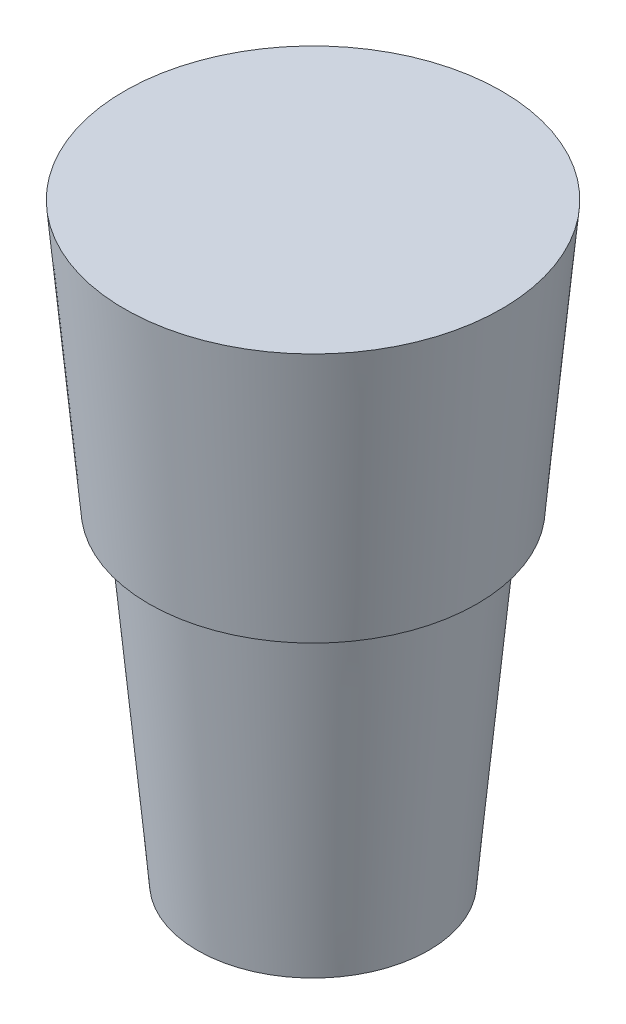
SolidWorks part; units mm, degrees
ref_plane "Front Plane" through (0, 0, 0) normal (0, 0, 1) x (1, 0, 0)
ref_plane "Top Plane" through (0, 0, 0) normal (0, 1, 0) x (1, 0, 0)
ref_plane "Right Plane" through (0, 0, 0) normal (1, 0, 0) x (0, 0, -1)
sketch "Sketch1" plane through (0, 0, 0) normal (0, 0, 1) x (1, 0, 0)
  line L0 (-15.8032, -39.107) -> (8.3268, -39.107)
  line L1 (8.3268, -39.107) -> (14.2743, 25.663)
  line L2 (14.2743, 25.663) -> (18.4356, 28.5767)
  line L3 (18.4356, 28.5767) -> (23.5668, 84.4567)
  line L4 (23.5668, 84.4567) -> (-15.8032, 84.4567)
  line L5 (-15.8032, -39.107) -> (-15.8032, 84.4567)
  line L6 (14.2743, 25.663) -> (-46.952, 25.663) construction
  dimension "D1" = 24.13
  dimension "D2" = 64.77
  dimension "D3" = 55.88
  dimension "D4" = 5.08
  dimension "D5" = 39.37
  dimension "D6" = 145
revolve "Revolve1" add sketch "Sketch1" angle 360 about L5
